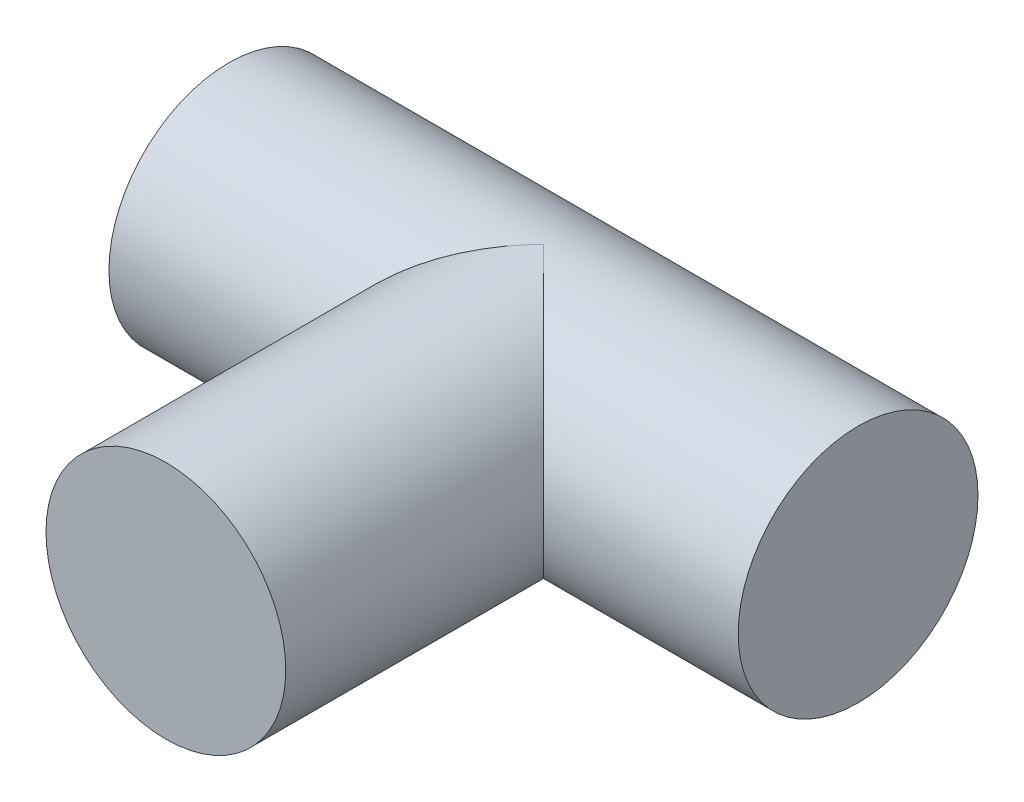
SolidWorks part; units mm, degrees
ref_plane "Alzado" through (0, 0, 0) normal (0, 0, 1) x (1, 0, 0)
ref_plane "Planta" through (0, 0, 0) normal (0, 1, 0) x (1, 0, 0)
ref_plane "Vista lateral" through (0, 0, 0) normal (1, 0, 0) x (0, 0, -1)
sketch "Croquis1" plane through (0, 0, 0) normal (0, 0, 1) x (1, 0, 0)
  circle A0 centre (0, 0) radius 9.525
  dimension "D1" = 19.05
extrude "Saliente-Extruir1" add sketch "Croquis1" along normal blind 30
sketch "Croquis2" plane through (0, 0, 0) normal (1, 0, 0) x (0, 0, -1)
  circle A0 centre (0, 0) radius 9.525
extrude "Saliente-Extruir2" add sketch "Croquis2" along normal mid plane 50
